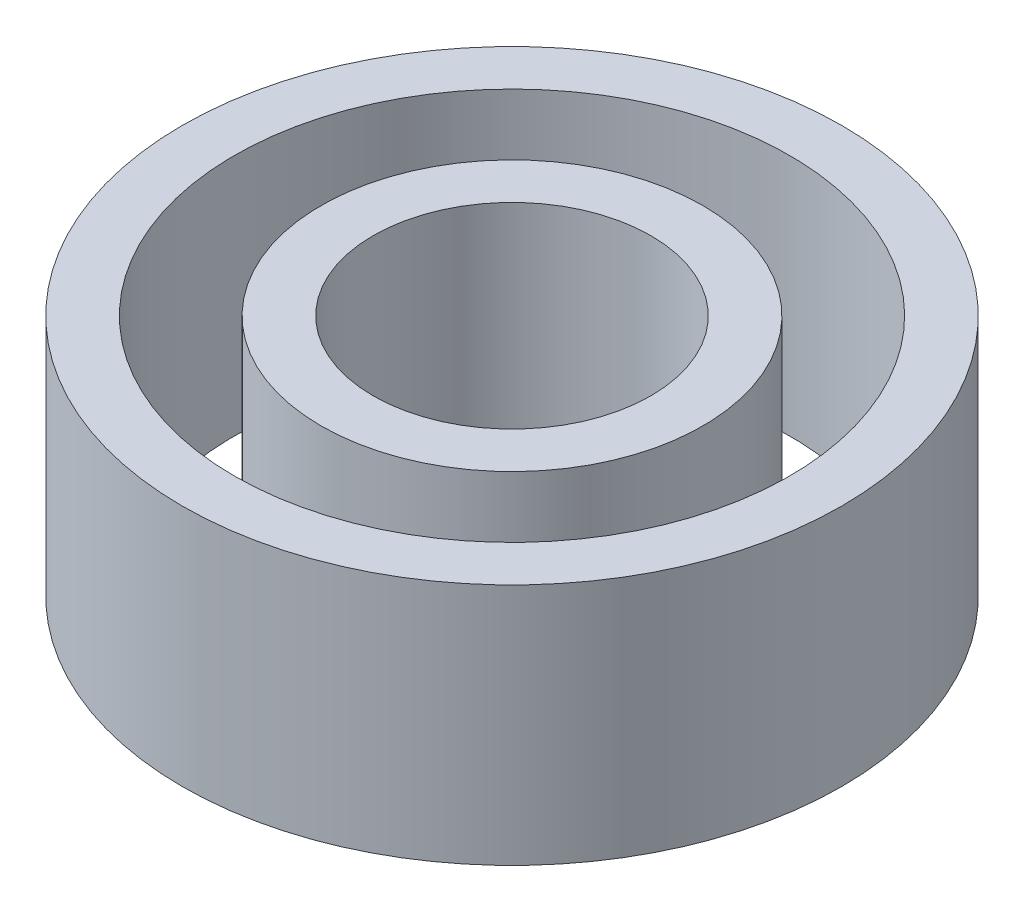
SolidWorks part; units mm, degrees
ref_plane "Front" through (0, 0, 0) normal (0, 0, 1) x (1, 0, 0)
ref_plane "Top" through (0, 0, 0) normal (0, 1, 0) x (1, 0, 0)
ref_plane "Right" through (0, 0, 0) normal (1, 0, 0) x (0, 0, -1)
sketch "Sketch1" plane through (0, 0, 0) normal (0, 1, 0) x (1, 0, 0)
  circle A0 centre (0, 0) radius 4
  circle A1 centre (0, 0) radius 9.5
  circle A2 centre (0, 0) radius 5.5
  circle A3 centre (0, 0) radius 8
  dimension "D1" = 8
  dimension "D2" = 19
  dimension "D3" = 1.5
  dimension "D4" = 1.5
extrude "Boss-Extrude1" add sketch "Sketch1" along normal blind 7 contours A2 A0 | A1 A3
